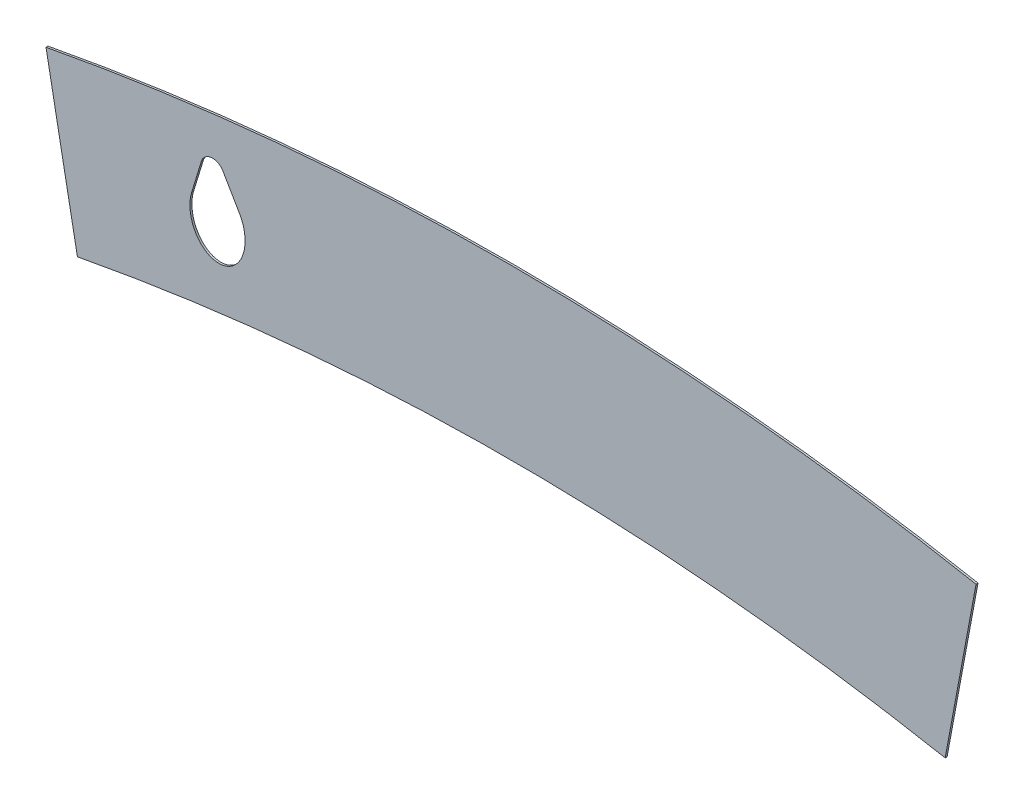
SolidWorks part; units mm, degrees
material "6061 Alloy"
ref_plane "front" through (0, 0, 0) normal (0, 0, 1) x (1, 0, 0)
ref_plane "top" through (0, 0, 0) normal (0, 1, 0) x (1, 0, 0)
ref_plane "right" through (0, 0, 0) normal (1, 0, 0) x (0, 0, -1)
sketch "Sketch1" plane through (0, 0, 0) normal (0, 0, 1) x (1, 0, 0)
  line L0 (0, 0) -> (0, -273.05) construction
  line L1 (0, 0) -> (383.281, 0) construction
  line L2 (-752.475, -70.8548) -> (-701.6242, -339.128)
  line L3 (752.475, -70.8548) -> (702.4878, -339.2922)
  line L4 (-492.125, -30.1529) -> (-460.7405, -301.4009) construction
  line L5 (-501.0337, -104.9984) -> (-516.777, -156.3841)
  line L6 (-466.3606, -100.9866) -> (-439.2993, -147.4196)
  arc A0 (752.475, -70.8548) -> (-752.475, -70.8548) centre (0, -4031.0562) ccw
  arc A1 (702.4878, -339.2922) -> (-701.6242, -339.128) centre (0, -4031.0562) ccw
  arc A3 (-466.3606, -100.9866) -> (-501.0337, -104.9984) centre (-482.8194, -110.5789) ccw
  ellipse E0 centre (-474.9735, -178.389) end of major axis (-481.3597, -123.1947) minor radius 44.45 (-516.777, -156.3841) -> (-439.2993, -147.4196) ccw
  dimension "D1" = 4031.0562
  dimension "D5" = 6.6
  dimension "D12" = 19.05
  dimension "D2" = 1504.95
  dimension "D3" = 273.05
  dimension "D4" = 701.6242
  dimension "D6" = 492.125
  dimension "D8" = 149.225
  dimension "D9" = 88.9
  dimension "D10" = 55.5625
  dimension "D11" = 752.475
  dimension "D13" = 702.4878
  dimension "D14" = 80.9625
extrude "Base-Extrude" add sketch "Sketch1" against normal blind 3.175
